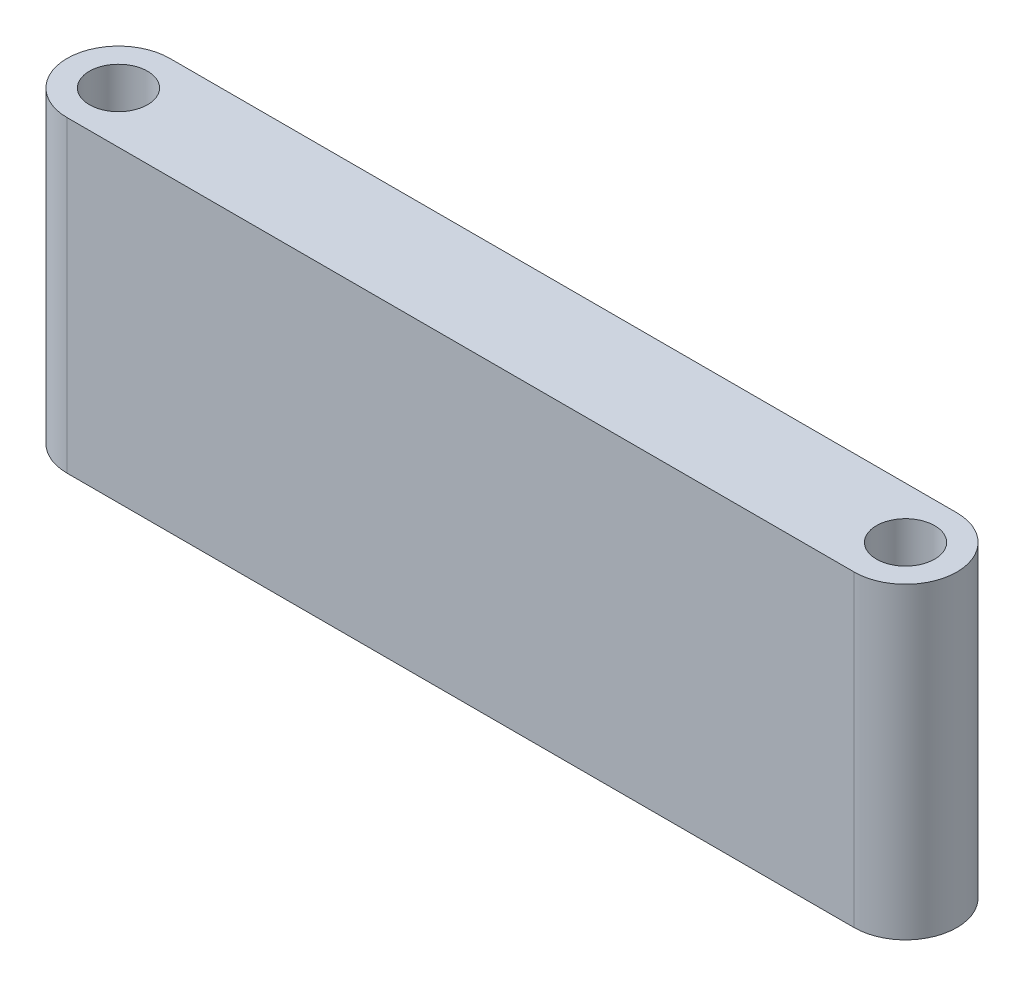
SolidWorks part; units mm, degrees
ref_plane "前视基准面" through (0, 0, 0) normal (0, 0, 1) x (1, 0, 0)
ref_plane "上视基准面" through (0, 0, 0) normal (0, 1, 0) x (1, 0, 0)
ref_plane "右视基准面" through (0, 0, 0) normal (1, 0, 0) x (0, 0, -1)
other "Configuration Table"
sketch "草图1" plane through (0, 0, 0) normal (0, 1, 0) x (1, 0, 0)
  line L0 (-23, 0) -> (23, 0) construction
  line L1 (-23, 3) -> (23, 3)
  line L2 (-23, -3) -> (23, -3)
  arc A0 (-23, 3) -> (-23, -3) centre (-23, 0) ccw
  arc A1 (23, -3) -> (23, 3) centre (23, 0) ccw
  circle A2 centre (23, 0) radius 1.7
  circle A3 centre (-23, 0) radius 1.7
  point P3 (0, 0)
  point P12 (13.7008, -3)
  dimension "D2" = 3.4
  dimension "D1" = 6
  dimension "D3" = 46
extrude "凸台-拉伸1" add sketch "草图1" along normal blind 18
